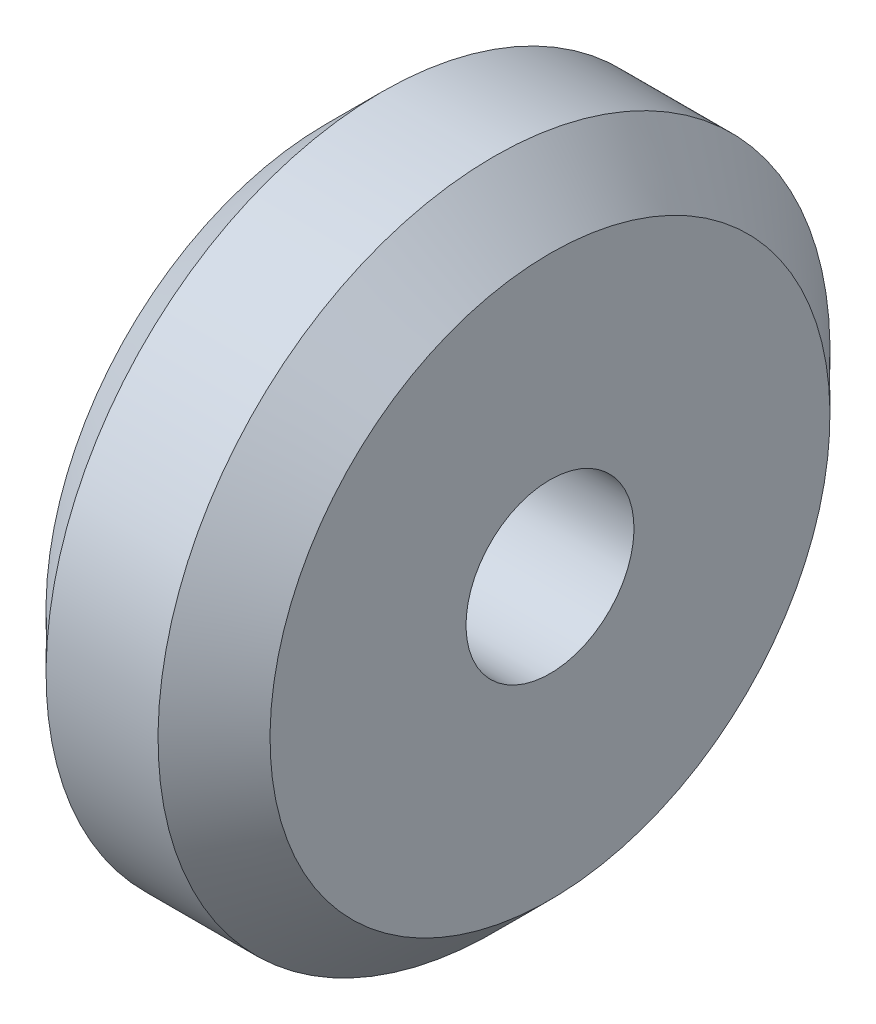
SolidWorks part; units mm, degrees
material "Nylon 6/10"
ref_plane "Front" through (0, 0, 0) normal (0, 0, 1) x (1, 0, 0)
ref_plane "Top" through (0, 0, 0) normal (0, 1, 0) x (1, 0, 0)
ref_plane "Right" through (0, 0, 0) normal (1, 0, 0) x (0, 0, -1)
sketch "Sketch1" plane through (0, 0, 0) normal (0, 0, 1) x (1, 0, 0)
  line L0 (0, 0) -> (0, 10)
  line L1 (0, 10) -> (2, 12)
  line L2 (2, 12) -> (6, 12)
  line L3 (6, 12) -> (8, 10)
  line L4 (8, 10) -> (8, 0)
  line L5 (8, 0) -> (0, 0)
  dimension "D1" = 8
  dimension "D2" = 45
  dimension "D3" = 12
  dimension "D4" = 10
  dimension "D5" = 10
revolve "Revolve1" add sketch "Sketch1" angle 360 about L5
sketch "Sketch2" plane through (8, 0, 0) normal (1, 0, 0) x (0, 0, -1)
  circle A0 centre (0, 0) radius 3
  dimension "D1" = 6
extrude "Cut-Extrude1" cut sketch "Sketch2" against normal blind 10
